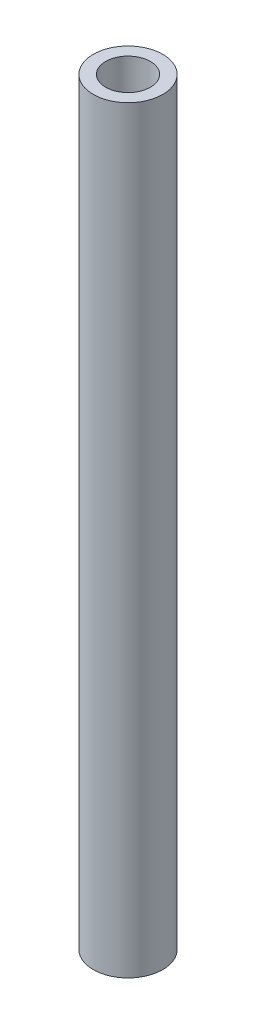
SolidWorks part; units mm, degrees
ref_plane "Piano frontale" through (0, 0, 0) normal (0, 0, 1) x (1, 0, 0)
ref_plane "Piano superiore" through (0, 0, 0) normal (0, 1, 0) x (1, 0, 0)
ref_plane "Piano destro" through (0, 0, 0) normal (1, 0, 0) x (0, 0, -1)
sketch "Schizzo1" plane through (0, 0, 0) normal (0, 1, 0) x (1, 0, 0)
  circle A0 centre (0, 0) radius 2.485
  dimension "D1" = 4.97
extrude "Estrusione-Estrusione1" add sketch "Schizzo1" along normal blind 54.2
hole_wizard "Foro per Vite M3-1" positions "Schizzo3" profile "Schizzo2" hole size "M3" standard "Ansi Metric"
sketch "Schizzo3" plane through (0, 54.2, 0) normal (0, 1, 0) x (1, 0, 0)
  point P0 (0, 0)
sketch "Schizzo2" plane through (0, 54.2, 0) normal (1, 0, 0) x (0, 0, 1)
  line L0 (0, 0) -> (0, 11.9614)
  line L1 (0, 11.9614) -> (1.6, 11)
  line L2 (1.6, 11) -> (1.6, 0)
  line L5 (1.6, 0) -> (0, 0)
  line L10 (0, 11.9614) -> (-1.6, 11) construction
  line L11 (0, -6.35) -> (0, 107.95) construction
  dimension "Hole Dia." = 3.2
  dimension "Hole Depth" = 11
  dimension "Drill Angle" = 118
